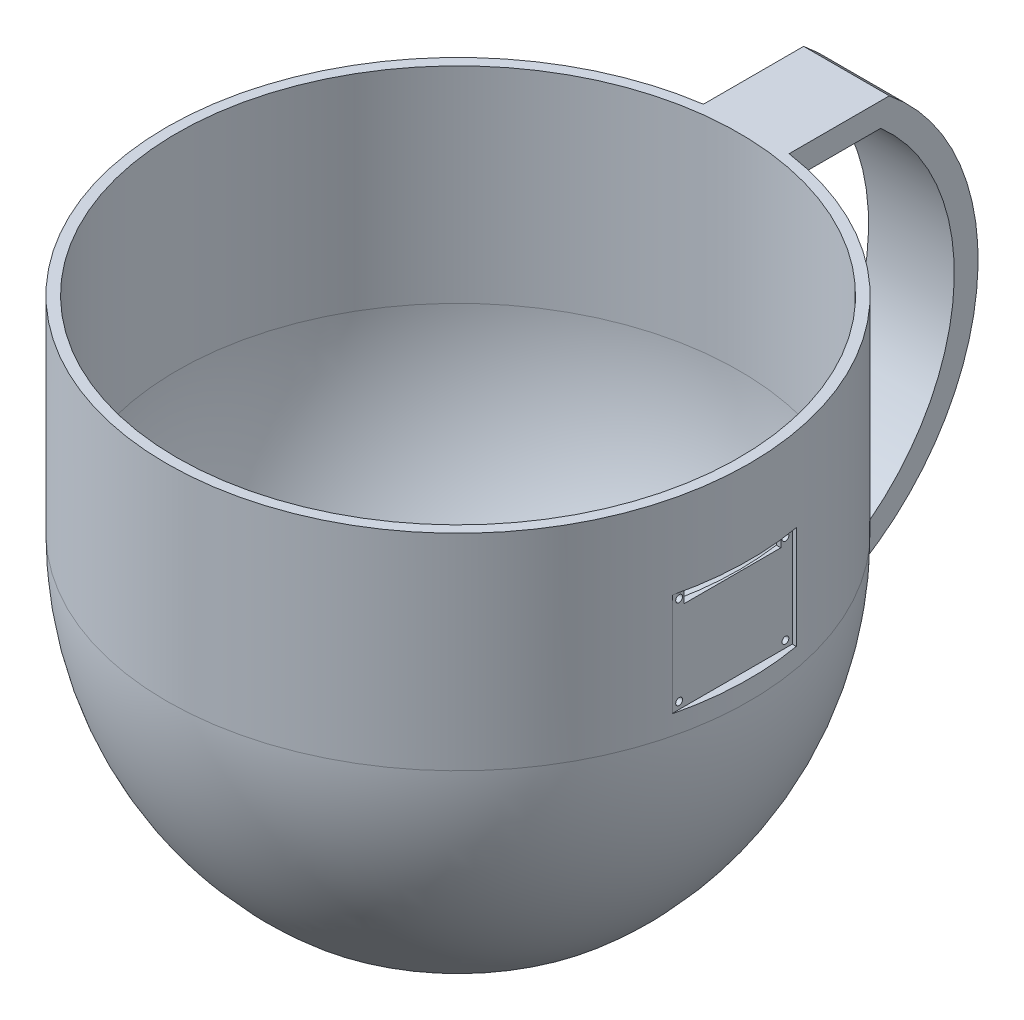
SolidWorks part; units mm, degrees
ref_plane "Front Plane" through (0, 0, 0) normal (0, 0, 1) x (1, 0, 0)
ref_plane "Top Plane" through (0, 0, 0) normal (0, 1, 0) x (1, 0, 0)
ref_plane "Right Plane" through (0, 0, 0) normal (1, 0, 0) x (0, 0, -1)
sketch "Sketch1" plane through (0, 0, 0) normal (0, 0, 1) x (1, 0, 0)
  line L0 (0, 0) -> (50, 0)
  line L1 (85, 135.9934) -> (85, 75.9934)
  line L2 (0, -632.4893) -> (0, 30991.9734) construction
  line L3 (82, 135.9934) -> (82, 75.9934)
  line L4 (0, 3) -> (48.8824, 3)
  line L5 (82, 135.9934) -> (85, 135.9934)
  line L6 (0, 3) -> (0, 0)
  arc A0 (50, 0) -> (85, 75.9934) centre (-15, 75.9934) ccw
  arc A1 (48.8824, 3) -> (82, 75.9934) centre (-15, 75.9934) ccw
  dimension "D3" = 100
  dimension "D1" = 60
  dimension "D2" = 50
  dimension "D4" = 85
  dimension "D5" = 3
revolve "Revolve1" add sketch "Sketch1" angle 360 about L6
sketch "Sketch5" plane through (0, 0, 0) normal (1, 0, 0) x (0, 0, -1)
  line L1 (-20, 111.6417) -> (15, 111.6417)
  line L2 (-20, 111.6417) -> (-20, 81.6417)
  line L3 (-20, 81.6417) -> (15, 81.6417)
  line L4 (15, 111.6417) -> (15, 81.6417)
  circle A0 centre (-18, 109.6417) radius 1
  circle A1 centre (13, 109.6417) radius 1
  circle A2 centre (-18, 83.6417) radius 1
  circle A3 centre (13, 83.6417) radius 1
  dimension "D4" = 2
  dimension "D5" = 2
  dimension "D6" = 2
  dimension "D7" = 2
  dimension "D8" = 2
  dimension "D1" = 35
  dimension "D2" = 30
  dimension "D3" = 15
extrude "Cut-Extrude1" cut sketch "Sketch5" against normal blind 7.5 from offset 90 contours L2 L1 L4 L3
sketch "Sketch6" plane through (0, 0, 0) normal (1, 0, 0) x (0, 0, -1)
  circle A0 centre (13, 109.6417) radius 1
  circle A1 centre (-18, 109.6417) radius 1
  circle A2 centre (13, 83.6417) radius 1
  circle A3 centre (-18, 83.6417) radius 1
extrude "Cut-Extrude2" cut sketch "Sketch6" along normal blind 200 contours A0 | A1 | A3 | A2
sketch "Sketch7" plane through (0, 0, 0) normal (1, 0, 0) x (0, 0, -1)
  line L0 (-20, 111.6417) -> (15, 111.6417) construction
  line L1 (-16.64, 111.6417) -> (11.6761, 111.6417)
  line L2 (-16.64, 111.6417) -> (-16.64, 107.6417)
  line L3 (-16.64, 107.6417) -> (11.6761, 107.6417)
  line L4 (11.6761, 111.6417) -> (11.6761, 107.6417)
  circle A0 centre (-18, 109.6417) radius 1 construction
  dimension "D2" = 4
  dimension "D3" = 4
  dimension "D4" = 4
  dimension "D5" = 1.36
  dimension "D6" = 4
  dimension "D7" = 1.3239
extrude "Cut-Extrude3" cut sketch "Sketch7" along normal blind 200 contours L2 L1 L4 L3
sketch "Sketch8" plane through (0, 0, 0) normal (1, 0, 0) x (0, 0, -1)
  line L0 (83.3129, 135.9934) -> (113.3129, 135.9934)
  line L1 (83.3129, 129.0514) -> (110.7786, 129.0514)
  line L2 (85, 135.9934) -> (113.3129, 135.9934) construction
  line L3 (85, 135.9934) -> (-85, 135.9934) construction
  line L4 (85, 129.0514) -> (110.7786, 129.0514) construction
  line L5 (-50, 0) -> (50, 0) construction
  line L6 (-85, 135.9934) -> (-85, 75.9934) construction
  line L7 (83.3129, 135.9934) -> (83.3129, 129.0514)
  line L8 (64.8354, 18.8285) -> (59.5309, 12.4104)
  arc A0 (113.3129, 135.9934) -> (59.5309, 12.4104) centre (69.2535, 81.6734) cw
  arc A1 (110.7786, 129.0514) -> (63.7768, 18.9119) centre (69.2535, 81.6734) cw construction
  arc A2 (110.7786, 129.0514) -> (64.8354, 18.8285) centre (69.2535, 81.6734) cw
  arc A3 (113.3129, 135.9934) -> (63.1733, 11.9961) centre (69.2535, 81.6734) cw construction
  dimension "D2" = 69.9421
  dimension "D3" = 63
  dimension "D4" = 18.8285
  dimension "D6" = 81.6734
  dimension "D7" = 154.2535
  dimension "D1" = 30
  dimension "D5" = 12.4104
extrude "Boss-Extrude1" add sketch "Sketch8" along normal mid plane 25 contours L8 A0 L0 L7 L1 A2
sketch "Sketch10" plane through (0, 0, 0) normal (0, 1, 0) x (1, 0, 0)
  line L0 (12.5, 113.3129) -> (-12.5, 113.3129) construction
  line L1 (11, 113.3129) -> (12.5, 113.3129)
  line L2 (11, 113.3129) -> (11, 84.0759)
  line L3 (11, 84.0759) -> (12.5, 84.0759)
  line L4 (12.5, 113.3129) -> (12.5, 84.0759)
  line L8 (-12.5, 113.3129) -> (-11, 113.3129)
  line L9 (-12.5, 113.3129) -> (-12.5, 84.0759)
  line L10 (-12.5, 84.0759) -> (-11, 84.0759)
  line L11 (-11, 113.3129) -> (-11, 84.0759)
  dimension "D1" = 29.237
  dimension "D2" = 1.5
  dimension "D3" = 29.237
  dimension "D4" = 1.5
